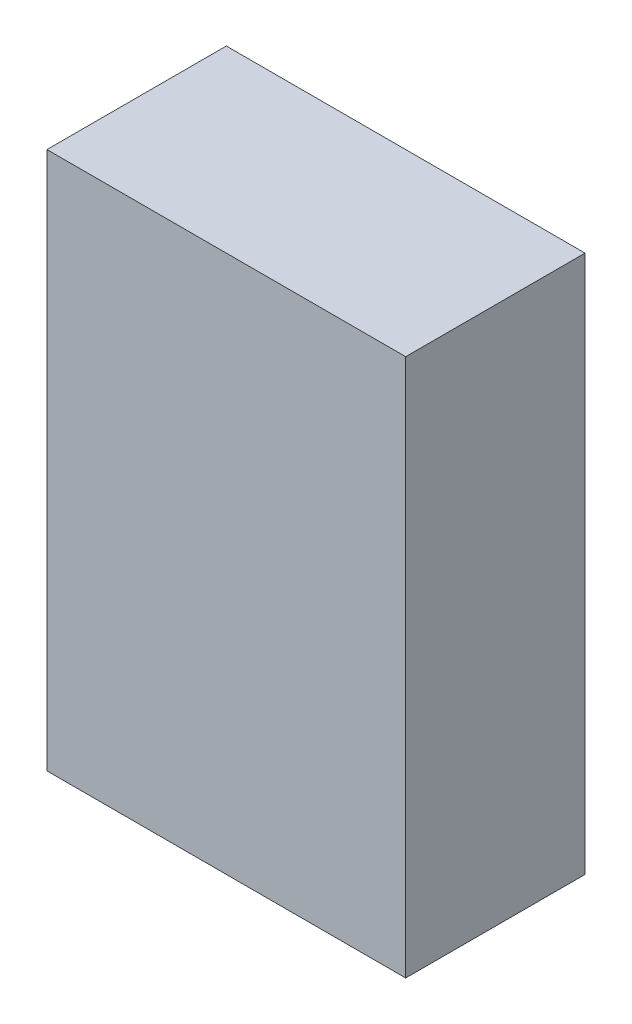
SolidWorks part; units mm, degrees
ref_plane "Front Plane" through (0, 0, 0) normal (0, 0, 1) x (1, 0, 0)
ref_plane "Top Plane" through (0, 0, 0) normal (0, 1, 0) x (1, 0, 0)
ref_plane "Right Plane" through (0, 0, 0) normal (1, 0, 0) x (0, 0, -1)
sketch "Sketch1" plane through (0, 0, 0) normal (0, 0, 1) x (1, 0, 0)
  line L1 (-10, -15) -> (10, -15)
  line L2 (-10, -15) -> (-10, 15)
  line L3 (-10, 15) -> (10, 15)
  line L4 (10, -15) -> (10, 15)
  dimension "D1" = 20
  dimension "D2" = 30
extrude "Boss-Extrude1" add sketch "Sketch1" along normal blind 10 separate body
